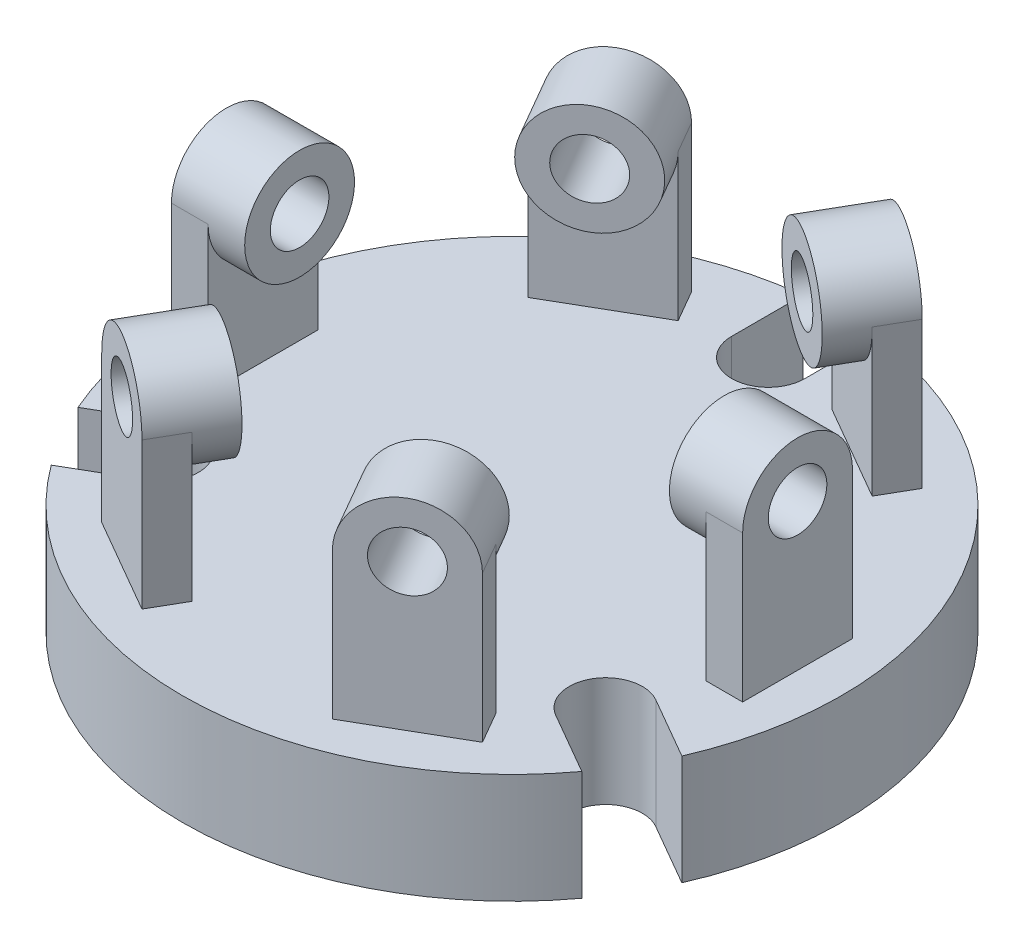
SolidWorks part; units mm, degrees
ref_plane "Front Plane" through (0, 0, 0) normal (0, 0, 1) x (1, 0, 0)
ref_plane "Top Plane" through (0, 0, 0) normal (0, 1, 0) x (1, 0, 0)
ref_plane "Right Plane" through (0, 0, 0) normal (1, 0, 0) x (0, 0, -1)
sketch "Sketch1" plane through (0, 0, 0) normal (0, 1, 0) x (1, 0, 0)
  circle A0 centre (0, 0) radius 45
  dimension "D1" = 90
extrude "Boss-Extrude1" add sketch "Sketch1" along normal blind 15
sketch "Sketch2" plane through (0, 15, 0) normal (0, 1, 0) x (1, 0, 0)
  line L0 (0, 0) -> (0, 52.9654) construction
  line L1 (-5, 35) -> (-5, 44.7214)
  line L2 (5, 35) -> (5, 44.7214)
  circle A0 centre (0, 0) radius 30 construction
  arc A1 (-5, 35) -> (5, 35) centre (0, 35) ccw
  circle A2 centre (0, 0) radius 45 construction
  arc A3 (5, 44.7214) -> (-5, 44.7214) centre (0, 0) ccw
  dimension "D1" = 60
  dimension "D2" = 10
extrude "Cut-Extrude1" cut sketch "Sketch2" against normal through all
pattern_circular "CirPattern1" count 3 over 360 about axis through (0, 0, 0) along (0, 1, 0) of "Cut-Extrude1"
ref_plane "Plane1" through (39, 0, 0) normal (1, 0, 0) x (0, 0, -1)
sketch "Sketch4" plane through (39, 0, 0) normal (1, 0, 0) x (0, 0, -1)
  line L0 (0, 0) -> (0, 36.1123) construction
  line L1 (-7.5, 35) -> (-7.5, 15)
  line L2 (7.5, 35) -> (7.5, 15)
  line L3 (44.7214, 15) -> (-18.0306, 15) construction
  line L4 (7.5, 15) -> (-7.5, 15)
  arc A0 (7.5, 35) -> (-7.5, 35) centre (0, 35) ccw
  circle A1 centre (0, 35) radius 4
  dimension "D1" = 15
  dimension "D2" = 8
  dimension "D3" = 35
extrude "Boss-Extrude2" add sketch "Sketch4" against normal blind 5
sketch "Sketch6" plane through (39, 0, 0) normal (1, 0, 0) x (0, 0, -1)
  circle A0 centre (0, 35) radius 7.5
  arc A1 (7.5, 35) -> (-7.5, 35) centre (0, 35) ccw construction
  circle A2 centre (0, 35) radius 4 construction
  circle A3 centre (0, 35) radius 4
extrude "Boss-Extrude3" add sketch "Sketch6" against normal blind 10
pattern_circular "CirPattern2" count 6 over 360 about axis through (0, 0, 0) along (0, 1, 0) of "Boss-Extrude2", "Boss-Extrude3"
